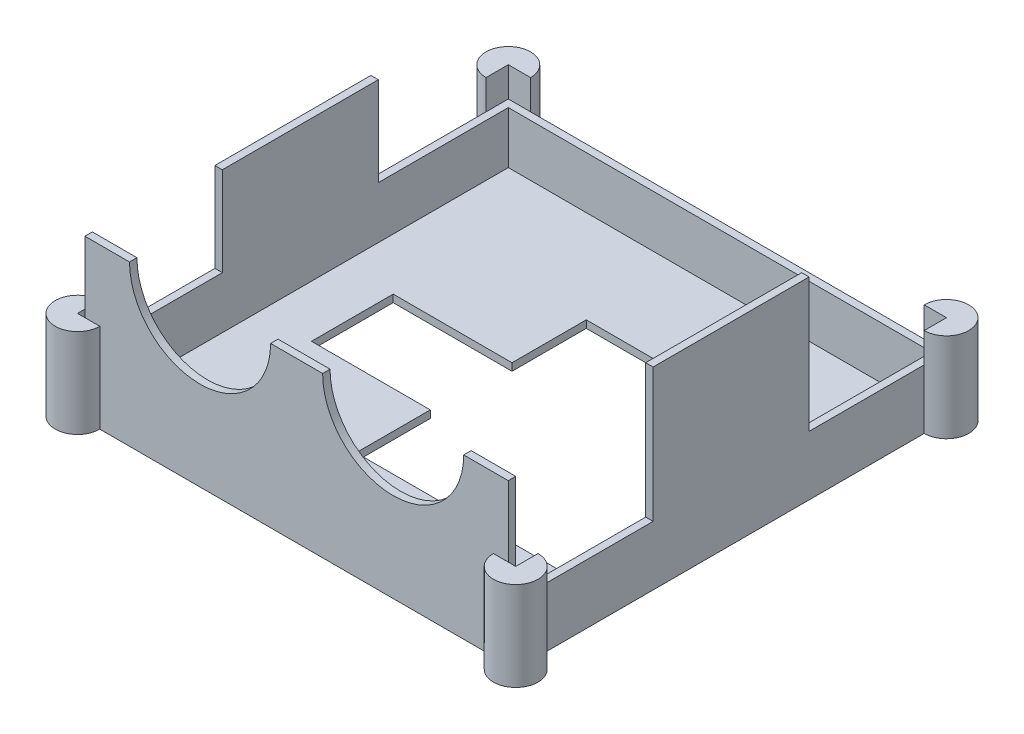
SolidWorks part; units mm, degrees
ref_plane "Front Plane" through (0, 0, 0) normal (0, 0, 1) x (1, 0, 0)
ref_plane "Top Plane" through (0, 0, 0) normal (0, 1, 0) x (1, 0, 0)
ref_plane "Right Plane" through (0, 0, 0) normal (1, 0, 0) x (0, 0, -1)
sketch "Sketch1" plane through (0, 0, 0) normal (0, 1, 0) x (1, 0, 0)
  line L1 (-29.5, -29) -> (29.5, -29)
  line L2 (-29.5, -29) -> (-29.5, 29)
  line L3 (-29.5, 29) -> (29.5, 29)
  line L4 (29.5, -29) -> (29.5, 29)
  line L5 (-29.5, -29) -> (29.5, 29) construction
  line L6 (-29.5, 29) -> (29.5, -29) construction
  point P0 (0, 0)
  dimension "D1" = 59
  dimension "D2" = 58
extrude "Boss-Extrude1" add sketch "Sketch1" along normal blind 1
sketch "Sketch2" plane through (0, 1, 0) normal (0, 1, 0) x (1, 0, 0)
  line L1 (-29.5, 29) -> (29.5, 29)
  line L2 (-29.5, 29) -> (-29.5, -29)
  line L3 (-29.5, -29) -> (29.5, -29)
  line L4 (29.5, 29) -> (29.5, -29)
  line L5 (-28.5, 28) -> (28.5, 28)
  line L6 (-28.5, 28) -> (-28.5, -28)
  line L7 (-28.5, -28) -> (28.5, -28)
  line L8 (28.5, 28) -> (28.5, -28)
  dimension "D1" = 1
  dimension "D2" = 1
  dimension "D3" = 1
  dimension "D4" = 1
extrude "Boss-Extrude2" add sketch "Sketch2" along normal blind 33
sketch "Sketch3" plane through (-29.5, 0, 0) normal (-1, 0, 0) x (0, 0, 1)
  line L0 (10.5, 8) -> (29, 8)
  line L5 (29, 34) -> (29, 0) construction
  line L7 (10.5, 8) -> (10.5, 20)
  line L8 (10.5, 20) -> (-10.5, 20)
  line L9 (-10.5, 20) -> (-10.5, 8)
  line L10 (-10.5, 8) -> (-29, 8)
  line L11 (-29, 34) -> (-29, 0) construction
  line L12 (-29, 0) -> (29, 0) construction
  line L15 (-29, 8) -> (-29, 34)
  line L16 (-29, 34) -> (29, 34)
  line L17 (29, 34) -> (29, 8)
  point P13 (0, 20)
  dimension "D1" = 21
  dimension "D2" = 20
  dimension "D3" = 8
extrude "Cut-Extrude1" cut sketch "Sketch3" against normal up to surface (1 mm away) up to face at (-28.5, 17.5, 0)
sketch "Sketch5" plane through (0, 0, 0) normal (0, -1, 0) x (1, 0, 0)
  line L0 (-21.5, 5.5) -> (-21.5, -5.5)
  line L1 (-21.5, -5.5) -> (-5.5, -5.5)
  line L2 (-5.5, -5.5) -> (-5.5, -15.5)
  line L3 (-5.5, -15.5) -> (25.5, -15.5)
  line L4 (25.5, -15.5) -> (25.5, 15.5)
  line L5 (25.5, 15.5) -> (-5.5, 15.5)
  line L6 (-5.5, 15.5) -> (-5.5, 5.5)
  line L7 (-5.5, 5.5) -> (-21.5, 5.5)
  line L8 (-29.5, -29) -> (-29.5, 29) construction
  line L9 (29.5, 29) -> (29.5, -29) construction
  point P2 (-21.5, 0)
  point P9 (25.5, 0)
  point P12 (-29.5, 0)
  point P13 (0, 0)
  dimension "D1" = 11
  dimension "D2" = 31
  dimension "D3" = 31
  dimension "D4" = 4
  dimension "D5" = 8
extrude "Cut-Extrude2" cut sketch "Sketch5" against normal up to surface (1 mm away) up to face at (0, 1, 0)
sketch "Sketch7" plane through (29.5, 0, 0) normal (1, 0, 0) x (0, 0, -1)
  line L0 (29, 8) -> (10.5, 8)
  line L1 (29, 34) -> (29, 0) construction
  line L2 (10.5, 8) -> (10.5, 26)
  line L3 (10.5, 26) -> (-10.5, 26)
  line L4 (-10.5, 26) -> (-10.5, 8)
  line L5 (-10.5, 8) -> (-29, 8)
  line L6 (-29, 34) -> (-29, 0) construction
  line L7 (-29, 8) -> (-29, 34)
  line L8 (-29, 34) -> (29, 34)
  line L9 (29, 34) -> (29, 8)
  line L10 (-29, 0) -> (29, 0) construction
  point P16 (0, 0)
  point P17 (0, 26)
  dimension "D1" = 8
  dimension "D2" = 21
  dimension "D3" = 26
extrude "Cut-Extrude3" cut sketch "Sketch7" against normal up to surface (1 mm away) up to face at (28.5, 17.5, 0)
sketch "Sketch8" plane through (0, 0, 29) normal (0, 0, 1) x (1, 0, 0)
  line L0 (28.5, 21.5) -> (22.5, 21.5)
  line L1 (28.5, 8) -> (28.5, 26) construction
  line L2 (3.5, 21.5) -> (-3.5, 21.5)
  line L3 (-22.5, 21.5) -> (-28.5, 21.5)
  line L4 (-28.5, 8) -> (-28.5, 34) construction
  line L5 (28.5, 8) -> (29.5, 8) construction
  line L6 (-28.5, 21.5) -> (-28.5, 34)
  line L7 (-28.5, 34) -> (28.5, 34)
  line L8 (28.5, 34) -> (28.5, 21.5)
  circle A0 centre (13, 21.5) radius 9.5
  circle A1 centre (-13, 21.5) radius 9.5
  point P17 (0, 21.5)
  line M5 (28.5, 8) -> (28.5, 34)
  line M6 (28.5, 34) -> (-28.5, 34)
  line M7 (-28.5, 34) -> (-28.5, 8)
  dimension "D1" = 13.5
  dimension "D2" = 19
  dimension "D3" = 7
  dimension "D4" = 13
extrude "Cut-Extrude4" cut sketch "Sketch8" against normal up to surface (1 mm away) contours A1 L2 A0 L0 L3 M5 M6 M7 | A1 | A0 up to face at (0, 14.3333, 28)
sketch "Sketch9" plane through (0, 0, -29) normal (0, 0, -1) x (-1, 0, 0)
  line L1 (28.5, 8) -> (-28.5, 8)
  line L2 (28.5, 8) -> (28.5, 34)
  line L3 (28.5, 34) -> (-28.5, 34)
  line L4 (-28.5, 8) -> (-28.5, 34)
extrude "Cut-Extrude5" cut sketch "Sketch9" against normal up to surface (1 mm away) up to face at (0, 14.3333, -28)
sketch "Sketch11" plane through (0, 0, 29) normal (0, 0, 1) x (1, 0, 0)
  line L1 (29.5, 0) -> (26.5, 0)
  line L2 (29.5, 0) -> (29.5, 12)
  line L3 (29.5, 12) -> (26.5, 12)
  line L4 (26.5, 0) -> (26.5, 12)
  dimension "D1" = 12
  dimension "D2" = 3
revolve "Revolve2" add sketch "Sketch11" angle 270 about L2
mirror "Mirror1" about plane through (0, 0, 0) normal (0, 0, 1) of "Revolve2"
mirror "Mirror2" about plane through (0, 0, 0) normal (1, 0, 0) of "Mirror1", "Revolve2"
